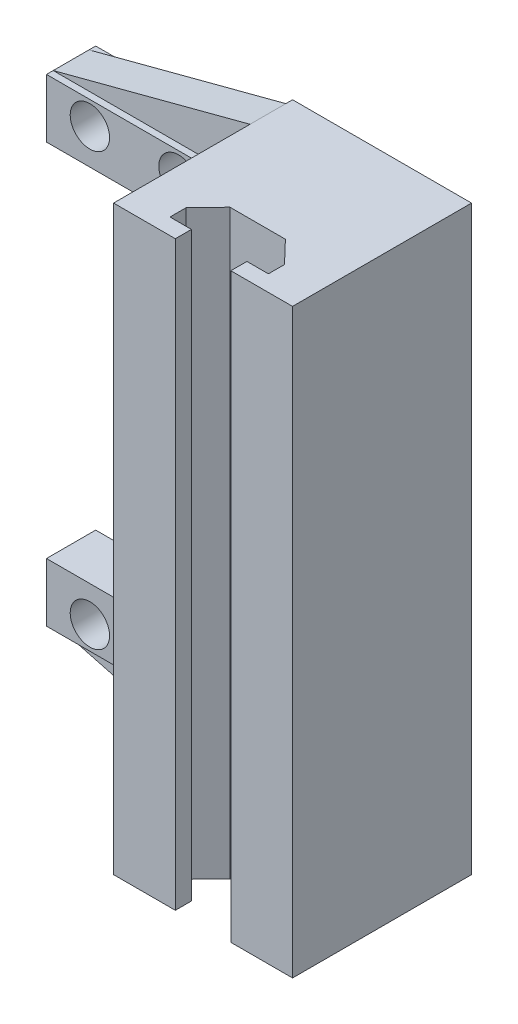
SolidWorks part; units mm, degrees
ref_plane "前视基准面" through (0, 0, 0) normal (0, 0, 1) x (1, 0, 0)
ref_plane "上视基准面" through (0, 0, 0) normal (0, 1, 0) x (1, 0, 0)
ref_plane "右视基准面" through (0, 0, 0) normal (1, 0, 0) x (0, 0, -1)
other "Configuration Table"
sketch "草图1" plane through (0, 0, 0) normal (0, 1, 0) x (1, 0, 0)
  line L3 (-30.2897, -35.0386) -> (-24.0897, -35.0386)
  line L4 (-37.1897, -21.1386) -> (-17.1897, -21.1386)
  line L5 (-37.1897, -21.1386) -> (-37.1897, -41.1386)
  line L6 (-37.1897, -41.1386) -> (-30.2897, -41.1386)
  line L7 (-17.1897, -21.1386) -> (-17.1897, -41.1386)
  line L8 (-32.6897, -39.3386) -> (-30.2897, -39.3386)
  line L9 (-30.2897, -39.3386) -> (-30.2897, -41.1386)
  line L10 (-24.0897, -39.3386) -> (-24.0897, -41.1386)
  line L11 (-32.6897, -39.3386) -> (-32.6897, -37.5386)
  line L12 (-32.6897, -37.5386) -> (-30.2897, -35.0386)
  line L13 (-21.6897, -39.3386) -> (-21.6897, -37.5386)
  line L14 (-21.6897, -37.5386) -> (-24.0897, -35.0386)
  line L15 (-24.0897, -39.3386) -> (-21.6897, -39.3386)
  line L16 (-24.0897, -41.1386) -> (-17.1897, -41.1386)
  dimension "D1" = 20
  dimension "D2" = 20
  dimension "D3" = 6.2
  dimension "D4" = 6.1
  dimension "D5" = 6.9
  dimension "D6" = 11
  dimension "D7" = 1.8
  dimension "D8" = 4.5
  dimension "D9" = 6.2
  dimension "D10" = 6.9
extrude "凸台-拉伸1" add sketch "草图1" along normal blind 65 contours L5 L6 L9 L8 L11 L12 L3 L14 L13 L15 L10 L16 L7 L4
sketch "草图2" plane through (-37.1897, 0, 0) normal (-1, 0, 0) x (0, 0, 1)
  line L0 (26.6386, 59.2) -> (21.1386, 59.2)
  line L1 (26.6386, 59.2) -> (26.6386, 52.65)
  line L2 (26.6386, 5.8) -> (21.1386, 5.8)
  line L3 (21.1386, 0) -> (41.1386, 0) construction
  line L4 (21.1386, 65) -> (21.1386, 0) construction
  line L5 (26.6386, 52.65) -> (21.1386, 52.65)
  line L6 (21.1386, 52.65) -> (21.1386, 59.2)
  line L7 (26.6386, 5.8) -> (26.6386, 12.35)
  line L8 (26.6386, 12.35) -> (21.1386, 12.35)
  line L9 (21.1386, 12.35) -> (21.1386, 5.8)
  line M6 (21.1386, 65) -> (21.1386, 0)
  dimension "D1" = 5.5
  dimension "D2" = 5.5
  dimension "D3" = 53.4
  dimension "D4" = 5.8
extrude "凸台-拉伸2" add sketch "草图2" along normal blind 20 contours L7 L8 L2 M6 | L6 L0 L1 L5
sketch "草图3" plane through (0, 0, 21.1386) normal (0, 0, -1) x (-1, 0, 0)
  line L0 (57.1897, 52.65) -> (57.1897, 59.2) construction
  line L1 (57.1897, 59.2) -> (37.1897, 59.2) construction
  line L2 (57.1897, 12.35) -> (57.1897, 5.8) construction
  line L3 (57.1897, 5.8) -> (37.1897, 5.8) construction
  circle A0 centre (54.3397, 56.6) radius 2.2
  circle A1 centre (44.4397, 56.6) radius 2.2
  circle A2 centre (44.4397, 8.4) radius 2.2
  circle A3 centre (54.3397, 8.4) radius 2.2
  dimension "D1" = 9.9
  dimension "D5" = 9.9
  dimension "D2" = 2.85
  dimension "D3" = 2.6
  dimension "D4" = 2.6
  dimension "D6" = 2.85
  dimension "D7" = 2.6
extrude "切除-拉伸1" cut sketch "草图3" against normal blind 20
sketch "草图4" plane through (-57.1897, 0, 0) normal (-1, 0, 0) x (0, 0, 1)
  line L1 (21.1386, 59.2) -> (26.6386, 59.2)
  line L2 (21.1386, 59.2) -> (21.1386, 52.65)
  line L3 (21.1386, 52.65) -> (26.6386, 52.65)
  line L4 (26.6386, 59.2) -> (26.6386, 52.65)
  line L5 (21.1386, 5.8) -> (26.6386, 5.8)
  line L6 (21.1386, 5.8) -> (21.1386, 12.35)
  line L7 (21.1386, 12.35) -> (26.6386, 12.35)
  line L8 (26.6386, 5.8) -> (26.6386, 12.35)
extrude "凸台-拉伸3" add sketch "草图4" along normal blind 2
ref_plane "基准面1" through (-37.1897, 59.2, 23.8886) normal (0, 0, -1) x (-1, 0, 0)
sketch "草图5" plane through (-37.1897, 59.2, 23.8886) normal (0, 0, -1) x (-1, 0, 0)
  line L0 (22, 0) -> (0, 5.8)
rib "筋7" sketch "草图5" sketch "草图5" thickness 4 extrusion direction parallel to sketch draft on no parameters "D1"=4
ref_plane "基准面2" through (-59.1897, 5.8, 23.8886) normal (0, 0, -1) x (-1, 0, 0)
sketch "草图6" plane through (-59.1897, 5.8, 23.8886) normal (0, 0, -1) x (-1, 0, 0)
  line L0 (0, 0) -> (-22, -5.8)
rib "筋8" sketch "草图6" sketch "草图6" thickness 4 extrusion direction parallel to sketch draft on no parameters "D1"=4
